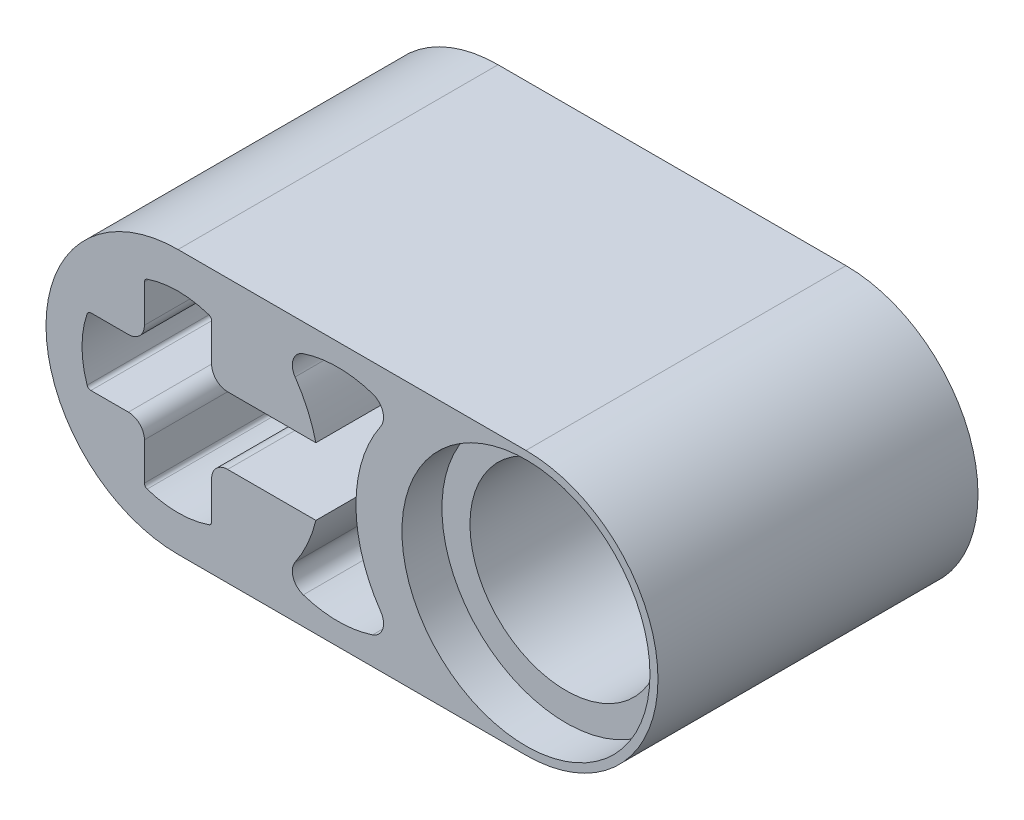
SolidWorks part; units mm, degrees
ref_plane "Front Plane" through (0, 0, 0) normal (0, 0, 1) x (1, 0, 0)
ref_plane "Top Plane" through (0, 0, 0) normal (0, 1, 0) x (1, 0, 0)
ref_plane "Right Plane" through (0, 0, 0) normal (1, 0, 0) x (0, 0, -1)
sketch "Sketch2" plane through (0, 0, 0) normal (0, 0, 1) x (1, 0, 0)
  line L32 (-6.0375, 0.84) -> (-6.9752, 0.84)
  line L33 (-5.6375, -2.1777) -> (-5.6375, -1.24)
  line L34 (-3.9575, -2.1777) -> (-3.9575, -1.24)
  line L35 (-2.6198, 0.84) -> (-3.5575, 0.84)
  line L36 (-2.6198, -0.84) -> (-3.5575, -0.84)
  line L37 (-5.6375, 1.24) -> (-5.6375, 2.1777)
  line L38 (-3.9575, 1.24) -> (-3.9575, 2.1777)
  line L39 (-6.0375, -0.84) -> (-6.9752, -0.84)
  line L40 (-2.5493, 0.84) -> (-1.3483, 0.84)
  line L41 (-2.5493, -0.84) -> (-1.3483, -0.84)
  line L42 (-2.6198, -0.84) -> (-2.5493, -0.84)
  line L43 (-2.6198, 0.84) -> (-2.5493, 0.84)
  line L44 (-4.7975, 3.3) -> (3.9, 3.3)
  line L46 (-4.7975, -3.3) -> (3.9, -3.3)
  circle A42 centre (3.9, 0) radius 2.4
  arc A43 (-1.666, -2.6101) -> (0.066, -2.6101) centre (-0.8, 0) ccw
  arc A44 (0.2701, -2.0046) -> (0.066, -2.6101) centre (-0.06, -2.2304) cw
  arc A45 (0.2701, -2.0046) -> (0.2701, 2.0046) centre (3.2, 0) cw
  arc A46 (0.2701, 2.0046) -> (0.066, 2.6101) centre (-0.06, 2.2304) ccw
  arc A47 (0.066, 2.6101) -> (-1.666, 2.6101) centre (-0.8, 0) ccw
  arc A48 (-1.8701, 2.0046) -> (-1.666, 2.6101) centre (-1.54, 2.2304) cw
  arc A49 (-1.8701, -2.0046) -> (-1.8701, 2.0046) centre (-4.8, 0) ccw
  arc A50 (-1.8701, -2.0046) -> (-1.666, -2.6101) centre (-1.54, -2.2304) ccw
  arc A51 (-4.0254, 2.2724) -> (-5.5697, 2.2724) centre (-4.7975, 0) ccw
  arc A52 (-7.0699, 0.7722) -> (-7.0699, -0.7722) centre (-4.7975, 0) ccw
  arc A53 (-5.5697, -2.2724) -> (-4.0254, -2.2724) centre (-4.7975, 0) ccw
  arc A54 (-5.6375, -1.24) -> (-6.0375, -0.84) centre (-6.0375, -1.24) ccw
  arc A55 (-3.9575, -1.24) -> (-3.5575, -0.84) centre (-3.5575, -1.24) cw
  arc A56 (-3.5575, 0.84) -> (-3.9575, 1.24) centre (-3.5575, 1.24) cw
  arc A57 (-6.0375, 0.84) -> (-5.6375, 1.24) centre (-6.0375, 1.24) ccw
  arc A58 (-6.9752, 0.84) -> (-7.0699, 0.7722) centre (-6.9752, 0.74) ccw
  arc A59 (-6.9752, -0.84) -> (-7.0699, -0.7722) centre (-6.9752, -0.74) cw
  arc A60 (-5.5697, -2.2724) -> (-5.6375, -2.1777) centre (-5.5375, -2.1777) cw
  arc A61 (-4.0254, -2.2724) -> (-3.9575, -2.1777) centre (-4.0575, -2.1777) ccw
  arc A62 (-4.0254, 2.2724) -> (-3.9575, 2.1777) centre (-4.0575, 2.1777) cw
  arc A63 (-5.6375, 2.1777) -> (-5.5697, 2.2724) centre (-5.5375, 2.1777) cw
  arc A64 (-1.3483, -0.84) -> (-1.3483, 0.84) centre (-4.7975, 0) ccw
  arc A67 (-4.7975, 3.3) -> (-4.7975, -3.3) centre (-4.7975, 0) ccw
  arc A68 (3.9, 3.3) -> (3.9, -3.3) centre (3.9, 0) cw
  point P4 (0, 0)
  point P62 (0.0138, 3.3)
  point P67 (0.0138, 3.3)
  point P70 (0.0138, -3.3)
  dimension "D3" = 4.8
extrude "Boss-Extrude1" add sketch "Sketch2" along normal blind 8 contours A68 L44 A67 L46 A42 L37 A63 A51 A62 L38 A56 L35 L43 L40 A49 A48 A47 A46 A45 A44 A43 A50 L41 L42 L36 A55 L34 A61 A53 A60 L33 A54 L39 A59 A52 A58 L32 A57
sketch "Sketch3" plane through (0, 0, 8) normal (0, 0, 1) x (1, 0, 0)
  circle A0 centre (3.9, 0) radius 3.1
  dimension "D1" = 6.2
extrude "Cut-Extrude1" cut sketch "Sketch3" against normal blind 1
ref_plane "Plane1" through (0, 0, 4) normal (0, 0, 1) x (1, 0, 0)
mirror "Mirror1" about plane through (0, 0, 4) normal (0, 0, 1) of "Cut-Extrude1"
